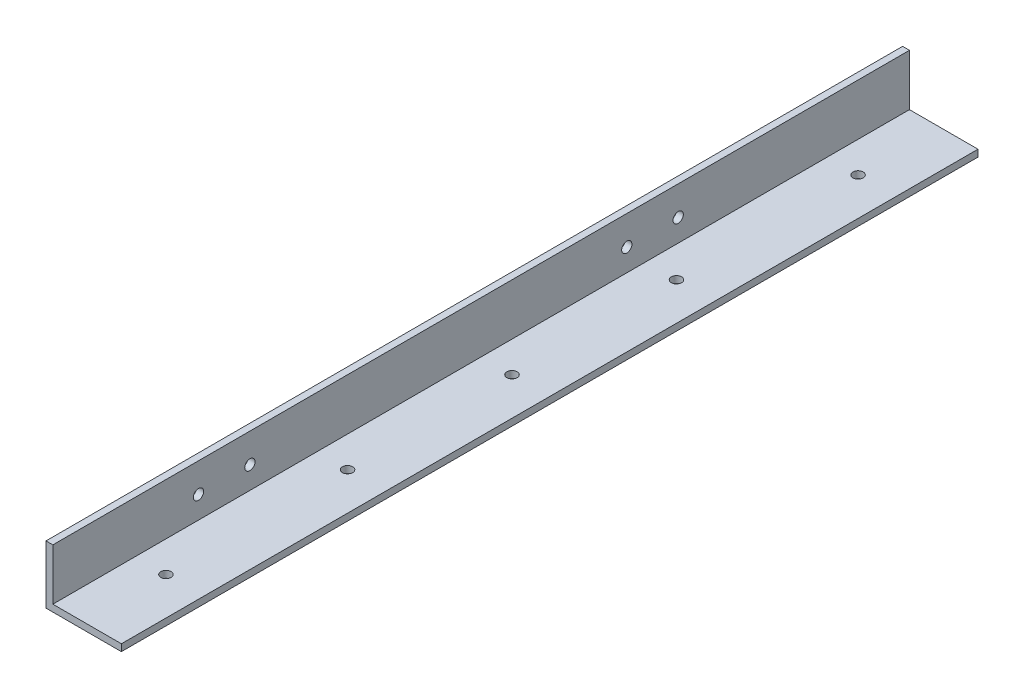
SolidWorks part; units mm, degrees
ref_plane "Front Plane" through (0, 0, 0) normal (0, 0, 1) x (1, 0, 0)
ref_plane "Top Plane" through (0, 0, 0) normal (0, 1, 0) x (1, 0, 0)
ref_plane "Right Plane" through (0, 0, 0) normal (1, 0, 0) x (0, 0, -1)
sketch "Sketch1" plane through (0, 0, 0) normal (0, 0, 1) x (1, 0, 0)
  line L0 (0, 0) -> (0, 17)
  line L1 (0, 17) -> (2, 17)
  line L2 (2, 17) -> (2, 2)
  line L3 (2, 2) -> (22, 2)
  line L4 (22, 2) -> (22, 0)
  line L5 (0, 0) -> (22, 0)
  dimension "D1" = 2
  dimension "D2" = 2
  dimension "D3" = 17
  dimension "D4" = 22
extrude "Boss-Extrude1" add sketch "Sketch1" against normal blind 250
sketch "Sketch2" plane through (0, 2, 0) normal (0, 1, 0) x (1, 0, 0)
  line L0 (11, 250) -> (11, 0) construction
  line L1 (22, 250) -> (2, 250) construction
  line L3 (0, 125) -> (22, 125) construction
  line L4 (0, 250) -> (0, 0) construction
  line L5 (22, 250) -> (22, 0) construction
  line L6 (22, 0) -> (2, 0) construction
  circle A0 centre (11, 226) radius 1.5
  circle A1 centre (11, 24) radius 1.5
  circle A2 centre (11, 125) radius 1.5
  circle A3 centre (11, 173) radius 1.5
  circle A4 centre (11, 77) radius 1.5
  dimension "D1" = 3
  dimension "D2" = 24
  dimension "D3" = 48
  dimension "D4" = 48
  dimension "D5" = 11
extrude "Cut-Extrude1" cut sketch "Sketch2" against normal blind 20
sketch "Sketch3" plane through (0, 0, 0) normal (-1, 0, 0) x (0, 0, 1)
  line L0 (-250, 8.5) -> (0, 8.5) construction
  line L1 (-250, 17) -> (-250, 0) construction
  line L2 (0, 17) -> (0, 0) construction
  line L3 (-125, -38.8376) -> (-125, 76.5538) construction
  line L4 (-250, 0) -> (0, 0) construction
  line L5 (-187.5, 25) -> (-162.5, 25) construction
  line L6 (-187.5, 25) -> (-187.5, 0) construction
  line L7 (-187.5, 0) -> (-162.5, 0) construction
  line L8 (-162.5, 25) -> (-162.5, 0) construction
  line L9 (-187.5, 25) -> (-162.5, 0) construction
  line L10 (-187.5, 0) -> (-162.5, 25) construction
  line L11 (-175, 12.5) -> (-175, 2.484) construction
  line L12 (-62.5, 25) -> (-37.5, 25) construction
  line L13 (-62.5, 25) -> (-62.5, 0) construction
  line L14 (-62.5, 0) -> (-37.5, 0) construction
  line L15 (-37.5, 25) -> (-37.5, 0) construction
  line L16 (-62.5, 25) -> (-37.5, 0) construction
  line L17 (-62.5, 0) -> (-37.5, 25) construction
  line L18 (-50, 12.5) -> (-50, 2.484) construction
  circle A0 centre (-182.5, 8.5) radius 1.5
  circle A1 centre (-167.5, 8.5) radius 1.5
  circle A2 centre (-42.5, 8.5) radius 1.5
  circle A3 centre (-57.5, 8.5) radius 1.5
  point P8 (-125, 8.5)
  point P9 (-175, 12.5)
  point P16 (-50, 12.5)
  dimension "D6" = 3
  dimension "D8" = 3
  dimension "D1" = 25
  dimension "D2" = 25
  dimension "D3" = 50
  dimension "D4" = 75
  dimension "D5" = 5
  dimension "D7" = 5
extrude "Cut-Extrude2" cut sketch "Sketch3" against normal blind 10
